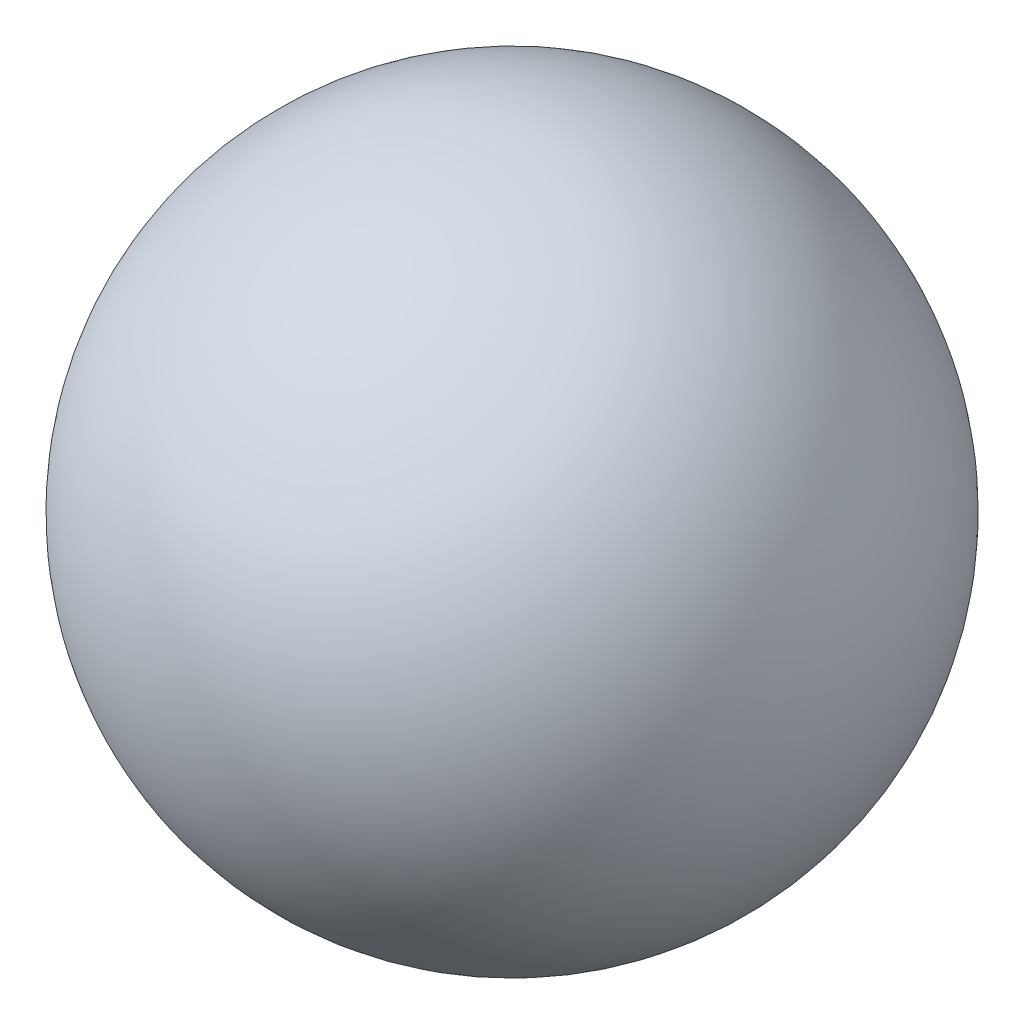
SolidWorks part; units mm, degrees
material "2.0375 (CuZn36Pb3)"
ref_plane "Front Plane" through (0, 0, 0) normal (0, 0, 1) x (1, 0, 0)
ref_plane "Top Plane" through (0, 0, 0) normal (0, 1, 0) x (1, 0, 0)
ref_plane "Right Plane" through (0, 0, 0) normal (1, 0, 0) x (0, 0, -1)
ref_plane "基准面1" through (0, 37.5, 0) normal (0, 1, 0) x (1, 0, 0)
sketch "草图1" plane through (0, 37.5, 0) normal (0, 1, 0) x (1, 0, 0)
  line L0 (5, 2.778) -> (5, -2.778)
  line L1 (5, 2.778) -> (5, -2.778) construction
  arc A0 (5, -2.778) -> (5, 2.778) centre (5, 0) ccw
revolve "旋转1" add sketch "草图1" angle 360 about L1
